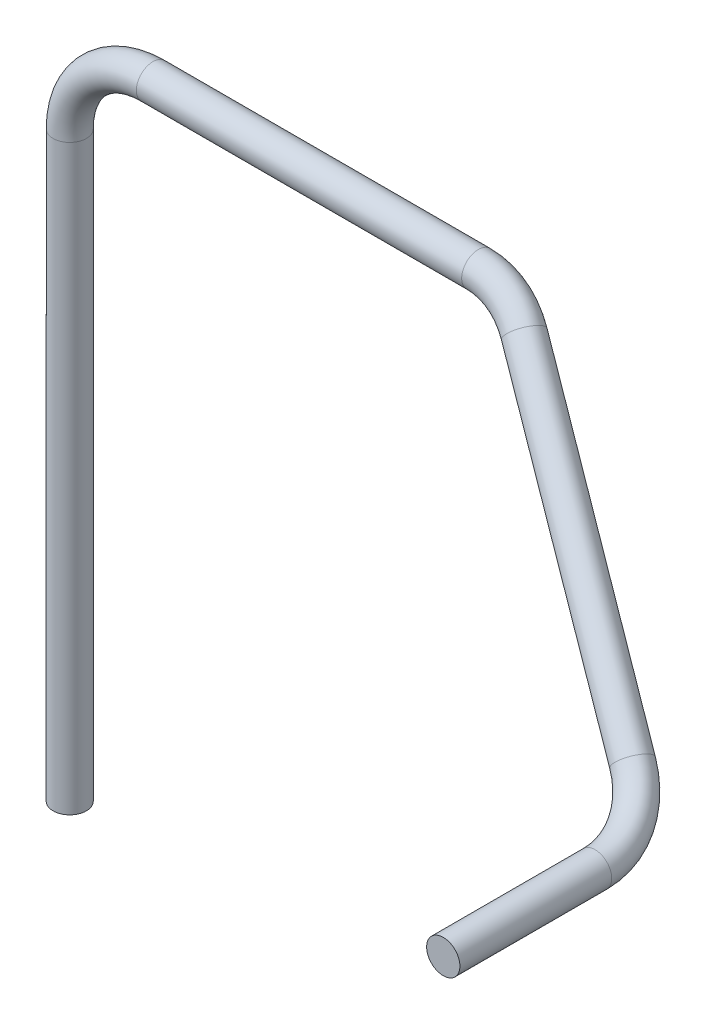
SolidWorks part; units mm, degrees
ref_plane "Front Plane" through (0, 0, 0) normal (0, 0, 1) x (1, 0, 0)
ref_plane "Top Plane" through (0, 0, 0) normal (0, 1, 0) x (1, 0, 0)
ref_plane "Right Plane" through (0, 0, 0) normal (1, 0, 0) x (0, 0, -1)
sketch3d "3DSketch1"
  line L0 (0, 0, 0) -> (0, 70, 0)
  line L1 (10, 80, 0) -> (49.1093, 80, 0)
  line L2 (56.1804, 77.5147, 1.5498) -> (83.8349, 54.0491, 16.1832)
  line L3 (88.6068, 50, 25.4568) -> (88.6068, 50, 43.7083)
  arc A0 (83.8349, 54.0491, 16.1832) -> (88.6068, 50, 25.4568) centre (80.9819, 56.47, 25.4568) ccw
  arc A1 (56.1804, 77.5147, 1.5498) -> (49.1093, 80, 0) centre (49.1093, 71.5147, 5.2915) ccw
  arc A2 (10, 80, 0) -> (0, 70, 0) centre (10, 70, 0) ccw
  point P6 (113.2155, 36.114, 18.1932)
  point P7 (116.0477, 34.9083, 30.4361)
  point P8 (120.4068, 32.3672, 75.3943)
  point P9 (61.2989, 79.7894, 0)
  point P10 (98.3792, 46.8533, 28.0371)
  point P13 (88.6068, 50, 18.7083)
  point P14 (74.5119, 48.845, 25.4568)
  point P17 (53.2515, 80, 0)
  point P18 (49.1093, 76.8062, 13.7768)
  point P21 (0, 80, 0)
  point P22 (10, 70, 10)
  dimension "D6" = 10
  dimension "D1" = 80
  dimension "D2" = 50
  dimension "D3" = 25
  dimension "D4" = 45
  dimension "D5" = 50
sketch "Sketch1" plane through (0, 0, 0) normal (0, 0, -1) x (1, 0, 0)
  line L0 (0, 0) -> (0, -60)
  line L1 (20, -80) -> (53.4315, -80)
  line L2 (67.5736, -74.1421) -> (91.2132, -50.5025)
  line L3 (97.0711, -36.3604) -> (97.0711, -19.6447)
  arc A0 (97.0711, -36.3604) -> (91.2132, -50.5025) centre (77.0711, -36.3604) cw
  arc A1 (67.5736, -74.1421) -> (53.4315, -80) centre (53.4315, -60) cw
  arc A2 (20, -80) -> (0, -60) centre (20, -60) cw
  point P8 (97.0711, -44.6447)
  point P12 (61.7157, -80)
  point P15 (0, -80)
  dimension "D2" = 25
  dimension "D3" = 50
  dimension "D5" = 20
  dimension "D1" = 80
  dimension "D4" = 45
sketch "Sketch2" plane through (0, 0, 0) normal (0, 1, 0) x (1, 0, 0)
  circle A0 centre (0, 0) radius 2
  dimension "D1" = 4
sweep "Sweep1" add profiles "Sketch2" path "3DSketch1"
